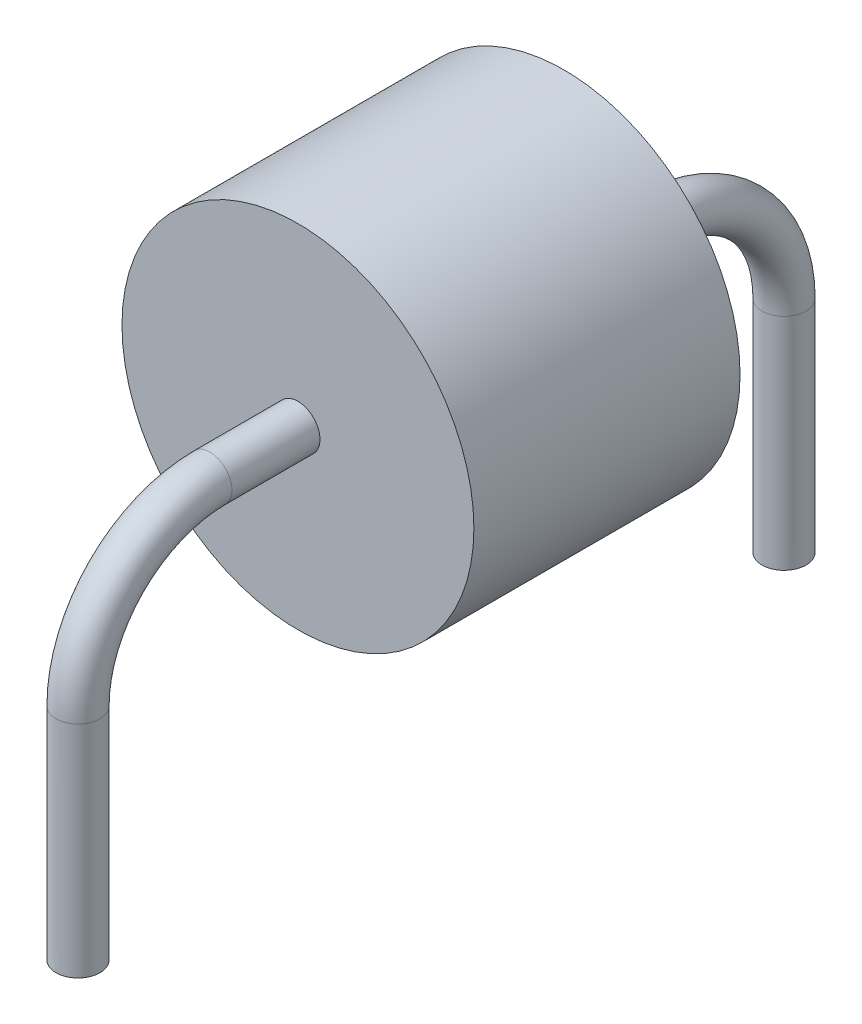
SolidWorks part; units mm, degrees
ref_plane "Front Plane" through (0, 0, 0) normal (0, 0, 1) x (1, 0, 0)
ref_plane "Top Plane" through (0, 0, 0) normal (0, 1, 0) x (1, 0, 0)
ref_plane "Right Plane" through (0, 0, 0) normal (1, 0, 0) x (0, 0, -1)
sketch "Sketch1" plane through (0, 0, 0) normal (0, 0, 1) x (1, 0, 0)
  circle A0 centre (0, 0) radius 4
  dimension "D1" = 8
extrude "Boss-Extrude1" add sketch "Sketch1" along normal mid plane 6.05
sketch "Sketch2" plane through (0, 0, 0) normal (1, 0, 0) x (0, 0, -1)
  line L0 (-3.025, 0) -> (-5.025, 0)
  line L1 (-3.025, 4) -> (-3.025, -4) construction
  line L2 (-8.025, -3) -> (-8.025, -8)
  arc A0 (-5.025, 0) -> (-8.025, -3) centre (-5.025, -3) ccw
  point P8 (-8.025, 0)
  dimension "D3" = 3
  dimension "D1" = 5
  dimension "D2" = 8
sketch "Sketch3" plane through (0, 0, 3.025) normal (0, 0, 1) x (1, 0, 0)
  circle A0 centre (0, 0) radius 0.5
  dimension "D1" = 1
sweep "Sweep1" add profiles "Sketch3" path "Sketch2"
mirror "Mirror1" about plane through (0, 0, 0) normal (0, 0, 1) of "Sweep1"
